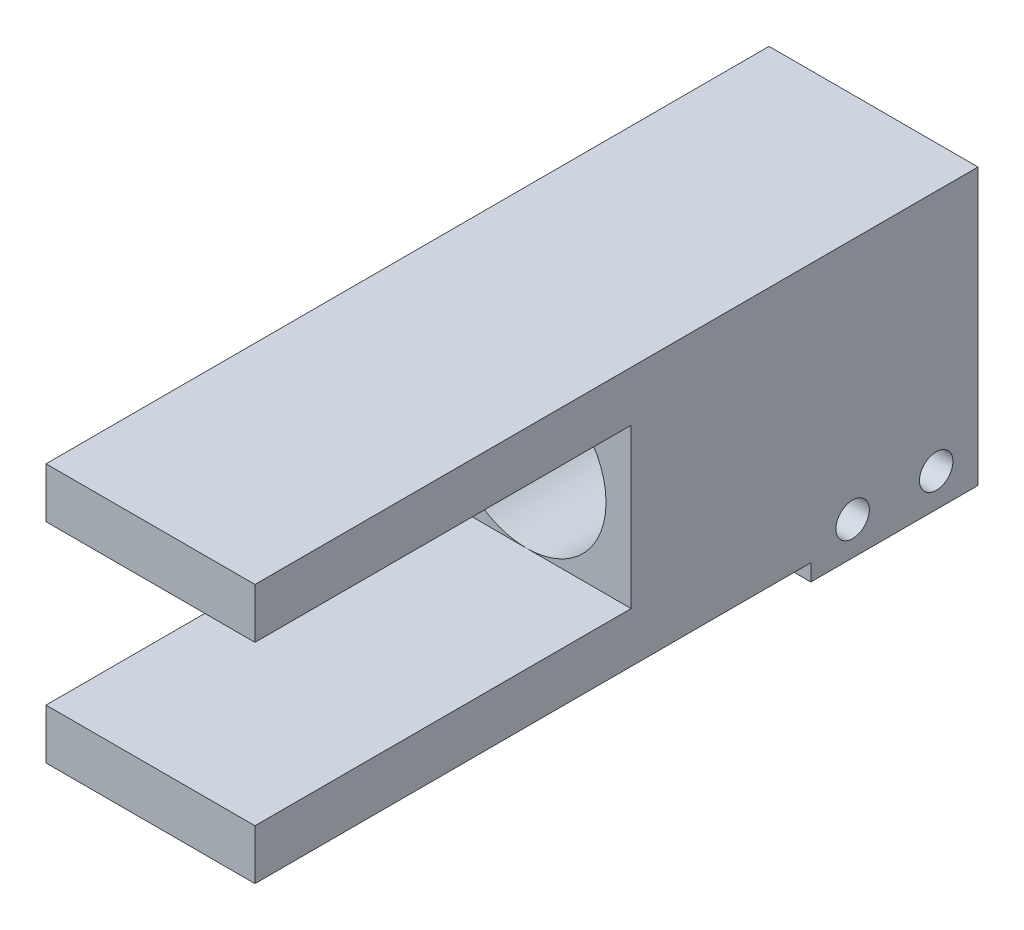
SolidWorks part; units mm, degrees
ref_plane "Front Plane" through (0, 0, 0) normal (0, 0, 1) x (1, 0, 0)
ref_plane "Top Plane" through (0, 0, 0) normal (0, 1, 0) x (1, 0, 0)
ref_plane "Right Plane" through (0, 0, 0) normal (1, 0, 0) x (0, 0, -1)
sketch "Sketch1" plane through (0, 0, 0) normal (1, 0, 0) x (0, 0, -1)
  line L0 (0, 0) -> (0, -33)
  line L1 (0, -33) -> (-20, -33)
  line L2 (-20, -33) -> (-20, -31)
  line L3 (-20, -31) -> (-86.5, -31)
  line L4 (-86.5, -31) -> (-86.5, -25)
  line L5 (-86.5, -25) -> (-41.5, -25)
  line L6 (-41.5, -25) -> (-41.5, -6)
  line L7 (-41.5, -6) -> (-86.5, -6)
  line L8 (-86.5, -6) -> (-86.5, 0)
  line L9 (-86.5, 0) -> (0, 0)
  dimension "D1" = 86.5
  dimension "D2" = 86.5
  dimension "D3" = 45
  dimension "D4" = 19
  dimension "D5" = 6
  dimension "D6" = 6
  dimension "D7" = 33
  dimension "D8" = 20
extrude "Boss-Extrude1" add sketch "Sketch1" along normal mid plane 25
sketch "Sketch2" plane through (0, 0, 41.5) normal (0, 0, 1) x (1, 0, 0)
  line L1 (-12.5, -6) -> (-12.5, -25) construction
  line L2 (12.5, -25) -> (-12.5, -25) construction
  circle A0 centre (0, -15.5) radius 9.5
  point P2 (0, 0)
  dimension "D1" = 19
  dimension "D2" = 12.5
  dimension "D3" = 9.5
extrude "Cut-Extrude1" cut sketch "Sketch2" against normal blind 24.5 contours A0
sketch "Sketch3" plane through (0, 0, 17) normal (0, 0, 1) x (1, 0, 0)
  circle A0 centre (0, -15.5) radius 7
  arc A1 (0, -6) -> (0, -25) centre (0, -15.5) ccw construction
  dimension "D1" = 14
extrude "Cut-Extrude2" cut sketch "Sketch3" against normal up to next contours A0
sketch "Sketch4" plane through (12.5, 0, 0) normal (1, 0, 0) x (0, 0, -1)
  line L0 (-20, -33) -> (0, -33) construction
  line L1 (0, -33) -> (0, 0) construction
  circle A0 centre (-15, -29) radius 2
  circle A1 centre (-5, -29) radius 2
  dimension "D1" = 4
  dimension "D2" = 4
  dimension "D3" = 4
  dimension "D6" = 10
  dimension "D4" = 4
  dimension "D5" = 5
extrude "Cut-Extrude3" cut sketch "Sketch4" against normal up to next contours A0 | A1
